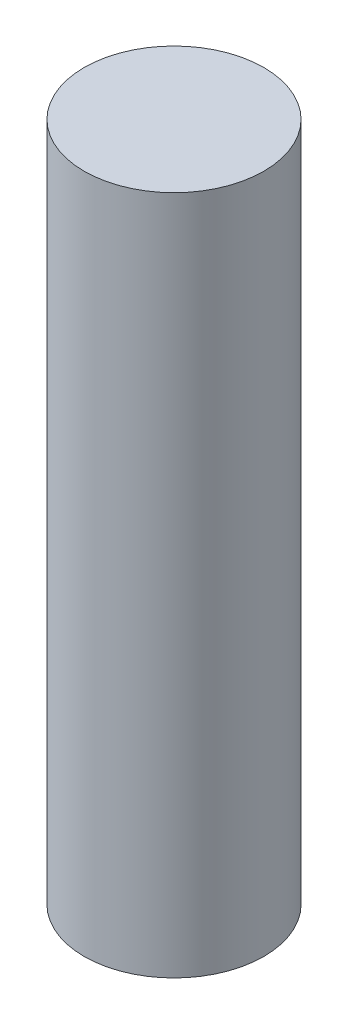
SolidWorks part; units mm, degrees
ref_plane "Front Plane" through (0, 0, 0) normal (0, 0, 1) x (1, 0, 0)
ref_plane "Top Plane" through (0, 0, 0) normal (0, 1, 0) x (1, 0, 0)
ref_plane "Right Plane" through (0, 0, 0) normal (1, 0, 0) x (0, 0, -1)
sketch "Sketch1" plane through (0, 0, 0) normal (0, 1, 0) x (1, 0, 0)
  circle A0 centre (0, 0) radius 12.55
  dimension "D1" = 25.1
extrude "Boss-Extrude1" add sketch "Sketch1" along normal blind 95
